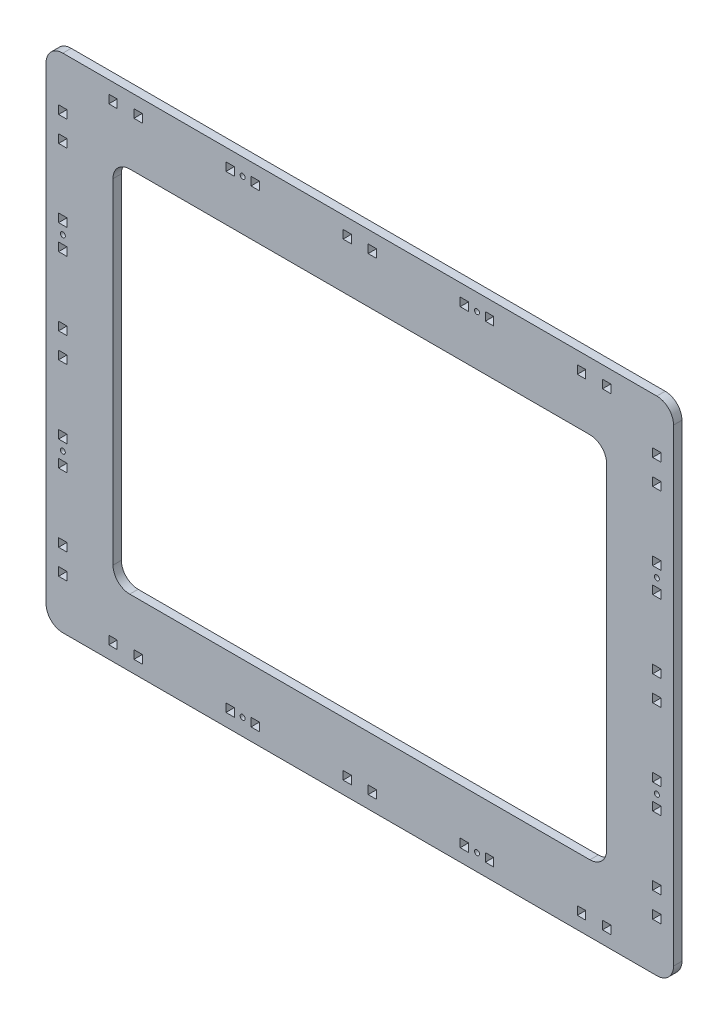
SolidWorks part; units mm, degrees
ref_plane "Front Plane" through (0, 0, 0) normal (0, 0, 1) x (1, 0, 0)
ref_plane "Top Plane" through (0, 0, 0) normal (0, 1, 0) x (1, 0, 0)
ref_plane "Right Plane" through (0, 0, 0) normal (1, 0, 0) x (0, 0, -1)
sketch "Sketch1" plane through (0, 0, 0) normal (0, 0, 1) x (1, 0, 0)
  line L0 (0, 0) -> (0, 150) construction
  line L1 (-177.5, -140) -> (177.5, -140) construction
  line L2 (-177.5, -140) -> (-177.5, 140) construction
  line L3 (-177.5, 140) -> (177.5, 140) construction
  line L4 (177.5, -140) -> (177.5, 140) construction
  line L5 (-177.5, -140) -> (177.5, 140) construction
  line L6 (-177.5, 140) -> (177.5, -140) construction
  line L7 (-187.5, -150) -> (187.5, -150)
  line L8 (-187.5, -150) -> (-187.5, 150)
  line L9 (-187.5, 150) -> (187.5, 150)
  line L11 (-187.5, -150) -> (187.5, 150) construction
  line L12 (-187.5, 150) -> (187.5, -150) construction
  line L13 (0, 0) -> (-187.5, 0) construction
  line L14 (-177.5, -5) -> (-177.5, 5) construction
  line L15 (-180, -5) -> (-180, -10)
  line L16 (-180, -5) -> (-175, -5)
  line L17 (-175, -5) -> (-175, -10)
  line L18 (-180, -10) -> (-175, -10)
  line L19 (-180, 5) -> (-180, 10)
  line L20 (-180, 5) -> (-175, 5)
  line L21 (-175, 5) -> (-175, 10)
  line L22 (-180, 10) -> (-175, 10)
  line L23 (-177.5, 0) -> (-184.4724, 0) construction
  line L24 (177.5, -61) -> (177.5, -51) construction
  line L33 (175, -61) -> (175, -66)
  line L34 (175, -61) -> (180, -61)
  line L43 (180, -61) -> (180, -66)
  line L44 (-177.5, 107) -> (-177.5, 117) construction
  line L45 (-180, 107) -> (-180, 102)
  line L46 (-180, 107) -> (-175, 107)
  line L47 (-175, 107) -> (-175, 102)
  line L48 (-180, 102) -> (-175, 102)
  line L49 (-180, 117) -> (-180, 122)
  line L50 (-180, 117) -> (-175, 117)
  line L51 (-175, 117) -> (-175, 122)
  line L52 (-180, 122) -> (-175, 122)
  line L53 (-177.5, 112) -> (-184.4724, 112) construction
  line L54 (-177.5, 51) -> (-177.5, 61) construction
  line L55 (-180, 51) -> (-180, 46)
  line L56 (-180, 51) -> (-175, 51)
  line L57 (-175, 51) -> (-175, 46)
  line L58 (-180, 46) -> (-175, 46)
  line L59 (-180, 61) -> (-180, 66)
  line L60 (-180, 61) -> (-175, 61)
  line L61 (-175, 61) -> (-175, 66)
  line L62 (-180, 66) -> (-175, 66)
  line L63 (-177.5, 56) -> (-184.4724, 56) construction
  line L64 (177.5, 56) -> (184.4724, 56) construction
  line L65 (177.5, 51) -> (177.5, 61) construction
  line L66 (177.5, 112) -> (184.4724, 112) construction
  line L67 (177.5, 107) -> (177.5, 117) construction
  line L68 (175, -66) -> (180, -66)
  line L69 (175, -51) -> (175, -46)
  line L70 (175, -51) -> (180, -51)
  line L71 (180, -51) -> (180, -46)
  line L72 (177.5, 0) -> (184.4724, 0) construction
  line L73 (177.5, -5) -> (177.5, 5) construction
  line L74 (180, 66) -> (175, 66)
  line L75 (175, 61) -> (175, 66)
  line L76 (180, 61) -> (175, 61)
  line L77 (180, 61) -> (180, 66)
  line L78 (180, 46) -> (175, 46)
  line L79 (175, 51) -> (175, 46)
  line L80 (180, 51) -> (175, 51)
  line L81 (180, 51) -> (180, 46)
  line L82 (180, 122) -> (175, 122)
  line L83 (175, 117) -> (175, 122)
  line L84 (180, 117) -> (175, 117)
  line L85 (180, 117) -> (180, 122)
  line L86 (180, 102) -> (175, 102)
  line L87 (175, 107) -> (175, 102)
  line L88 (180, 107) -> (175, 107)
  line L89 (180, 107) -> (180, 102)
  line L106 (180, 10) -> (175, 10)
  line L107 (175, 5) -> (175, 10)
  line L108 (180, 5) -> (175, 5)
  line L109 (180, 5) -> (180, 10)
  line L110 (180, -10) -> (175, -10)
  line L111 (175, -5) -> (175, -10)
  line L112 (180, -5) -> (175, -5)
  line L113 (180, -5) -> (180, -10)
  line L114 (-145, 140) -> (-135, 140) construction
  line L115 (-145, 142.5) -> (-150, 142.5)
  line L116 (-145, 142.5) -> (-145, 137.5)
  line L117 (-145, 137.5) -> (-150, 137.5)
  line L118 (-150, 142.5) -> (-150, 137.5)
  line L119 (-135, 142.5) -> (-130, 142.5)
  line L120 (-135, 142.5) -> (-135, 137.5)
  line L121 (-135, 137.5) -> (-130, 137.5)
  line L122 (-130, 142.5) -> (-130, 137.5)
  line L123 (-140, 140) -> (-140, 149.4724) construction
  line L124 (-75, 140) -> (-65, 140) construction
  line L125 (-75, 142.5) -> (-80, 142.5)
  line L126 (-75, 142.5) -> (-75, 137.5)
  line L127 (-75, 137.5) -> (-80, 137.5)
  line L128 (-80, 142.5) -> (-80, 137.5)
  line L129 (-65, 142.5) -> (-60, 142.5)
  line L130 (-65, 142.5) -> (-65, 137.5)
  line L131 (-65, 137.5) -> (-60, 137.5)
  line L132 (-60, 142.5) -> (-60, 137.5)
  line L133 (-70, 140) -> (-70, 149.4724) construction
  line L134 (-5, 140) -> (5, 140) construction
  line L135 (-5, 142.5) -> (-10, 142.5)
  line L136 (-5, 142.5) -> (-5, 137.5)
  line L137 (-5, 137.5) -> (-10, 137.5)
  line L138 (-10, 142.5) -> (-10, 137.5)
  line L139 (5, 142.5) -> (10, 142.5)
  line L140 (5, 142.5) -> (5, 137.5)
  line L141 (5, 137.5) -> (10, 137.5)
  line L142 (10, 142.5) -> (10, 137.5)
  line L143 (0, 140) -> (0, 149.4724) construction
  line L144 (65, 140) -> (75, 140) construction
  line L145 (65, 142.5) -> (60, 142.5)
  line L146 (65, 142.5) -> (65, 137.5)
  line L147 (65, 137.5) -> (60, 137.5)
  line L148 (60, 142.5) -> (60, 137.5)
  line L149 (75, 142.5) -> (80, 142.5)
  line L150 (75, 142.5) -> (75, 137.5)
  line L151 (75, 137.5) -> (80, 137.5)
  line L152 (80, 142.5) -> (80, 137.5)
  line L153 (70, 140) -> (70, 149.4724) construction
  line L154 (135, 140) -> (145, 140) construction
  line L155 (135, 142.5) -> (130, 142.5)
  line L156 (135, 142.5) -> (135, 137.5)
  line L157 (135, 137.5) -> (130, 137.5)
  line L158 (130, 142.5) -> (130, 137.5)
  line L159 (145, 142.5) -> (150, 142.5)
  line L160 (145, 142.5) -> (145, 137.5)
  line L161 (145, 137.5) -> (150, 137.5)
  line L162 (150, 142.5) -> (150, 137.5)
  line L163 (140, 140) -> (140, 149.4724) construction
  line L164 (135, -140) -> (145, -140) construction
  line L165 (65, -140) -> (75, -140) construction
  line L166 (-5, -140) -> (5, -140) construction
  line L167 (-75, -140) -> (-65, -140) construction
  line L168 (-145, -140) -> (-135, -140) construction
  line L169 (150, -142.5) -> (150, -137.5)
  line L170 (145, -137.5) -> (150, -137.5)
  line L171 (145, -142.5) -> (145, -137.5)
  line L172 (145, -142.5) -> (150, -142.5)
  line L173 (130, -142.5) -> (130, -137.5)
  line L174 (135, -137.5) -> (130, -137.5)
  line L175 (135, -142.5) -> (135, -137.5)
  line L176 (135, -142.5) -> (130, -142.5)
  line L177 (80, -142.5) -> (80, -137.5)
  line L178 (75, -137.5) -> (80, -137.5)
  line L179 (75, -142.5) -> (75, -137.5)
  line L180 (75, -142.5) -> (80, -142.5)
  line L181 (60, -142.5) -> (60, -137.5)
  line L182 (65, -137.5) -> (60, -137.5)
  line L183 (65, -142.5) -> (65, -137.5)
  line L184 (65, -142.5) -> (60, -142.5)
  line L185 (10, -142.5) -> (10, -137.5)
  line L186 (5, -137.5) -> (10, -137.5)
  line L187 (5, -142.5) -> (5, -137.5)
  line L188 (5, -142.5) -> (10, -142.5)
  line L189 (-10, -142.5) -> (-10, -137.5)
  line L190 (-5, -137.5) -> (-10, -137.5)
  line L191 (-5, -142.5) -> (-5, -137.5)
  line L192 (-5, -142.5) -> (-10, -142.5)
  line L193 (-60, -142.5) -> (-60, -137.5)
  line L194 (-65, -137.5) -> (-60, -137.5)
  line L195 (-65, -142.5) -> (-65, -137.5)
  line L196 (-65, -142.5) -> (-60, -142.5)
  line L197 (-80, -142.5) -> (-80, -137.5)
  line L198 (-75, -137.5) -> (-80, -137.5)
  line L199 (-75, -142.5) -> (-75, -137.5)
  line L200 (-75, -142.5) -> (-80, -142.5)
  line L201 (-130, -142.5) -> (-130, -137.5)
  line L202 (-135, -137.5) -> (-130, -137.5)
  line L203 (-135, -142.5) -> (-135, -137.5)
  line L204 (-135, -142.5) -> (-130, -142.5)
  line L205 (-150, -142.5) -> (-150, -137.5)
  line L206 (-145, -137.5) -> (-150, -137.5)
  line L207 (-145, -142.5) -> (-145, -137.5)
  line L208 (-145, -142.5) -> (-150, -142.5)
  line L209 (175, -46) -> (180, -46)
  line L210 (-137.5, -110) -> (137.5, -110)
  line L211 (-147.5, -100) -> (-147.5, 100)
  line L212 (-137.5, 110) -> (137.5, 110)
  line L213 (147.5, -100) -> (147.5, 100)
  line L214 (-147.5, -110) -> (147.5, 110) construction
  line L215 (-147.5, 110) -> (147.5, -110) construction
  line L216 (177.5, -56) -> (170.5276, -56) construction
  line L217 (177.5, -117) -> (177.5, -107) construction
  line L218 (175, -117) -> (175, -122)
  line L219 (175, -117) -> (180, -117)
  line L220 (180, -117) -> (180, -122)
  line L221 (175, -122) -> (180, -122)
  line L222 (175, -107) -> (175, -102)
  line L223 (175, -107) -> (180, -107)
  line L224 (180, -107) -> (180, -102)
  line L225 (175, -102) -> (180, -102)
  line L226 (177.5, -112) -> (170.5276, -112) construction
  line L227 (-177.5, -117) -> (-177.5, -107) construction
  line L228 (-180, -117) -> (-180, -122)
  line L229 (-180, -117) -> (-175, -117)
  line L230 (-175, -117) -> (-175, -122)
  line L231 (-180, -122) -> (-175, -122)
  line L232 (-180, -107) -> (-180, -102)
  line L233 (-180, -107) -> (-175, -107)
  line L234 (-175, -107) -> (-175, -102)
  line L235 (-180, -102) -> (-175, -102)
  line L236 (-177.5, -112) -> (-184.4724, -112) construction
  line L237 (-177.5, -61) -> (-177.5, -51) construction
  line L238 (-180, -61) -> (-180, -66)
  line L239 (-180, -61) -> (-175, -61)
  line L240 (-175, -61) -> (-175, -66)
  line L241 (-180, -66) -> (-175, -66)
  line L242 (-180, -51) -> (-180, -46)
  line L243 (-180, -51) -> (-175, -51)
  line L244 (-175, -51) -> (-175, -46)
  line L245 (-180, -46) -> (-175, -46)
  line L246 (-177.5, -56) -> (-184.4724, -56) construction
  line L247 (187.5, 150) -> (187.5, -150)
  circle A4 centre (-177.5, 56) radius 1.5
  circle A5 centre (177.5, 56) radius 1.5
  circle A11 centre (-70, 140) radius 1.5
  circle A13 centre (70, 140) radius 1.5
  circle A14 centre (70, -140) radius 1.5
  circle A15 centre (-70, -140) radius 1.5
  circle A16 centre (177.5, -56) radius 1.5
  circle A19 centre (-177.5, -56) radius 1.5
  arc A20 (-137.5, -110) -> (-147.5, -100) centre (-137.5, -100) cw
  arc A21 (147.5, -100) -> (137.5, -110) centre (137.5, -100) cw
  arc A22 (147.5, 100) -> (137.5, 110) centre (137.5, 100) ccw
  arc A23 (-137.5, 110) -> (-147.5, 100) centre (-137.5, 100) ccw
  point P0 (0, 0)
  point P6 (0, 0)
  dimension "D6" = 56
  dimension "D14" = 5
  dimension "D18" = 5
  dimension "D22" = 5
  dimension "D26" = 3
  dimension "D34" = 40
  dimension "D38" = 3
  dimension "D42" = 5
  dimension "D46" = 3
  dimension "D50" = 10
  dimension "D13" = 3
  dimension "D17" = 56
  dimension "D54" = 3
  dimension "D58" = 10
  dimension "D1" = 355
  dimension "D2" = 280
  dimension "D3" = 10
  dimension "D5" = 5
  dimension "D7" = 5
  dimension "D8" = 10
  dimension "D9" = 56
  dimension "D10" = 56
  dimension "D11" = 56
  dimension "D12" = 5
  dimension "D15" = 10
  dimension "D16" = 5
  dimension "D19" = 10
  dimension "D20" = 56
  dimension "D21" = 5
  dimension "D23" = 5
  dimension "D24" = 10
  dimension "D25" = 5
  dimension "D27" = 5
  dimension "D28" = 10
  dimension "D29" = 70
  dimension "D30" = 70
  dimension "D31" = 70
  dimension "D32" = 70
  dimension "D33" = 5
  dimension "D35" = 5
  dimension "D36" = 10
  dimension "D37" = 5
  dimension "D39" = 5
  dimension "D40" = 10
  dimension "D41" = 5
  dimension "D43" = 5
  dimension "D44" = 10
  dimension "D45" = 5
  dimension "D47" = 5
  dimension "D48" = 10
  dimension "D49" = 5
  dimension "D51" = 5
  dimension "D52" = 10
  dimension "D53" = 5
  dimension "D55" = 5
  dimension "D56" = 10
  dimension "D57" = 40
  dimension "D59" = 10
extrude "Boss-Extrude2" add sketch "Sketch1" along normal blind 5
fillet "Fillet1" radius 10 4 edges at (-187.5, -150, 2.5) (187.5, -150, 2.5) (-187.5, 150, 2.5) (187.5, 150, 2.5)
